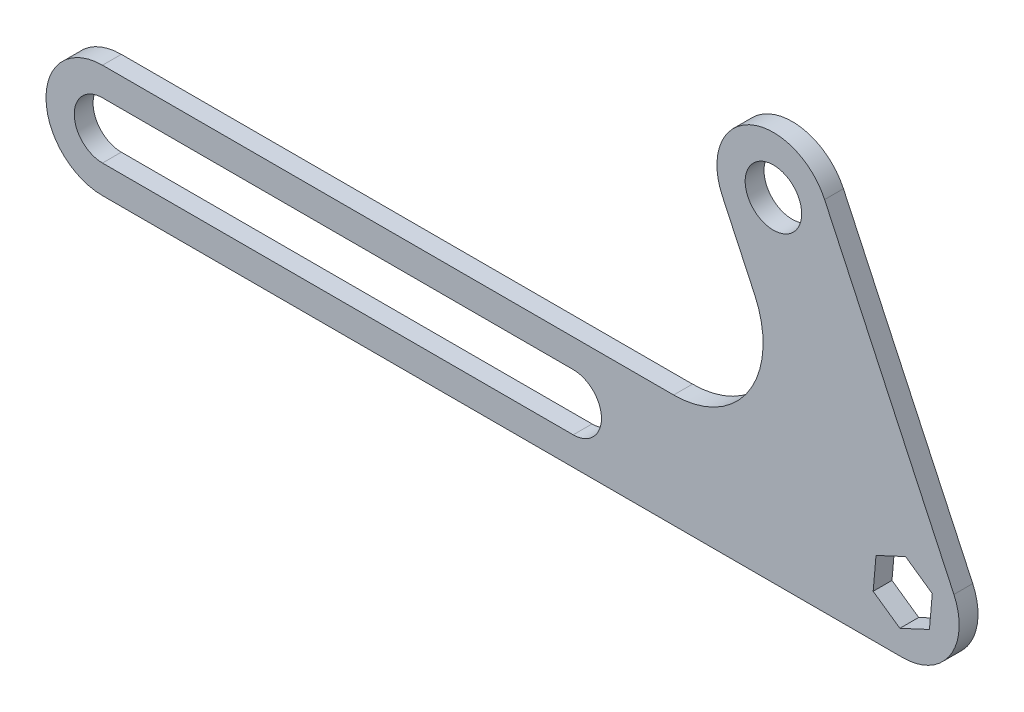
SolidWorks part; units mm, degrees
ref_plane "Front Plane" through (0, 0, 0) normal (0, 0, 1) x (1, 0, 0)
ref_plane "Top Plane" through (0, 0, 0) normal (0, 1, 0) x (1, 0, 0)
ref_plane "Right Plane" through (0, 0, 0) normal (1, 0, 0) x (0, 0, -1)
sketch "Sketch2" plane through (0, 0, 0) normal (0, 0, 1) x (1, 0, 0)
  line L0 (-170, 0) -> (0, 0) construction
  line L1 (-170, 12) -> (-48.6603, 12)
  line L2 (-170, -12) -> (0, -12)
  line L3 (0, 0) -> (-27.4702, 58.91) construction
  line L5 (10.8757, 5.0714) -> (-16.5945, 63.9814)
  line L6 (-170, 0) -> (-70, 0) construction
  line L7 (-170, 6) -> (-70, 6)
  line L8 (-170, -6) -> (-70, -6)
  line L9 (-31.4404, 39.0297) -> (-38.3459, 53.8386)
  line L10 (6.2791, 2.928) -> (0.6038, 6.9018)
  line L11 (0.6038, 6.9018) -> (-5.6753, 3.9739)
  line L12 (-5.6753, 3.9739) -> (-6.2791, -2.928)
  line L13 (-6.2791, -2.928) -> (-0.6038, -6.9018)
  line L14 (-0.6038, -6.9018) -> (5.6753, -3.9739)
  line L15 (5.6753, -3.9739) -> (6.2791, 2.928)
  arc A0 (-170, 12) -> (-170, -12) centre (-170, 0) ccw
  arc A1 (0, -12) -> (10.8757, 5.0714) centre (0, 0) ccw
  arc A2 (0, -12) -> (10.8757, 5.0714) centre (0, 0) ccw
  arc A3 (-16.5945, 63.9814) -> (-38.3459, 53.8386) centre (-27.4702, 58.91) ccw
  arc A4 (-170, 6) -> (-170, -6) centre (-170, 0) ccw
  arc A5 (-70, -6) -> (-70, 6) centre (-70, 0) ccw
  circle A6 centre (-27.4702, 58.91) radius 6
  arc A7 (-31.4404, 39.0297) -> (-48.6603, 12) centre (-48.6603, 31) cw
  arc A9 (-6, 0) -> (-5.9772, 0.5229) centre (0, 0) ccw construction
  point P15 (-120, 0)
  dimension "D1" = 12
  dimension "D2" = 12
  dimension "D3" = 12
  dimension "D7" = 19
  dimension "D9" = 6
  dimension "D4" = 65
  dimension "D6" = 65
  dimension "D8" = 12
  dimension "D10" = 100
  dimension "D5" = 70
extrude "Boss-Extrude1" add sketch "Sketch2" along normal blind 4 contours L9 A7 L1 A0 L2 A1 L5 A3 L15 L14 L13 L12 L11 L10 A5 L8 A4 L7 A6
equation "\"s\"= 100"
equation "\"D10@Sketch2\"=\"s\""
